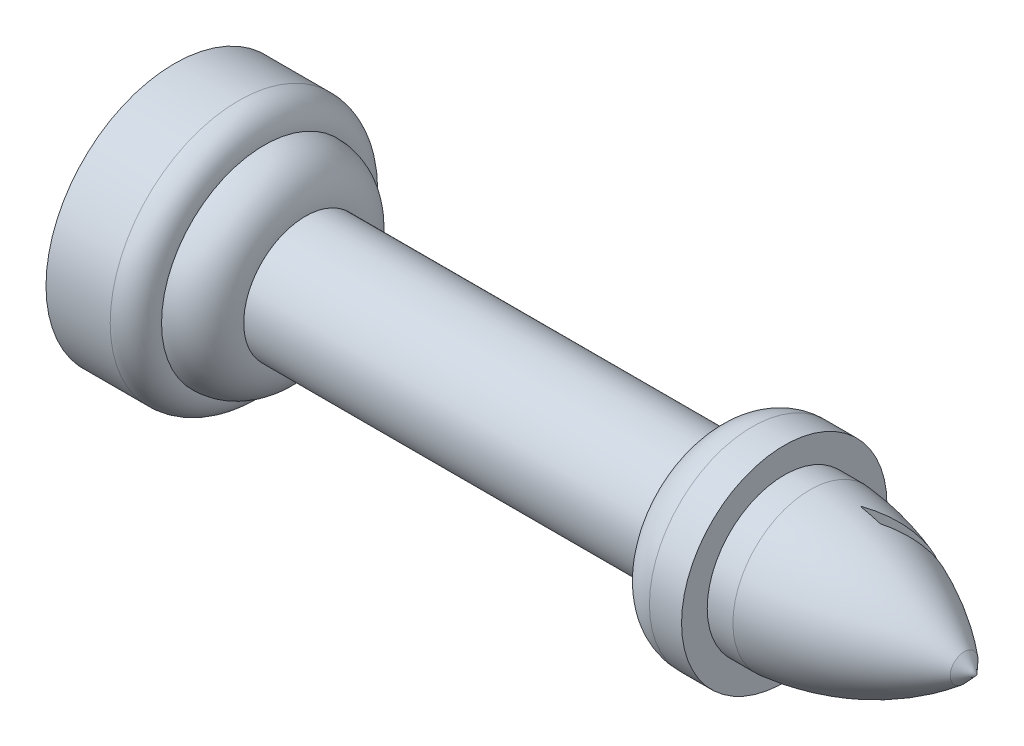
SolidWorks part; units mm, degrees
ref_plane "Спереди" through (0, 0, 0) normal (0, 0, 1) x (1, 0, 0)
ref_plane "Сверху" through (0, 0, 0) normal (0, 1, 0) x (1, 0, 0)
ref_plane "Справа" through (0, 0, 0) normal (1, 0, 0) x (0, 0, -1)
sketch "попа" plane through (0, 0, 0) normal (0, 1, 0) x (1, 0, 0)
  line L0 (0, 0) -> (0, 10)
  line L1 (0, 10) -> (5, 10)
  line L2 (5, 10) -> (5, 0)
  line L3 (-5.61, 0) -> (5.61, 0) construction
  line L5 (7, 0) -> (7, 8)
  line L6 (10.2, 4.8) -> (10.2, 0)
  line L7 (1, 5.25) -> (1, 0)
  line L8 (1, 5.25) -> (3.5, 5.25)
  line L9 (3.5, 5.25) -> (3.5, 0)
  line L10 (0, 0) -> (10.2, 0)
  arc A0 (5, 10) -> (7, 8) centre (5, 8) cw
  arc A1 (7, 8) -> (10.2, 4.8) centre (7, 4.8) cw
  dimension "D3" = 2
  dimension "D5" = 3.2
  dimension "D1" = 10
  dimension "D2" = 5
  dimension "D4" = 2
  dimension "D6" = 4.8
  dimension "D7" = 1
  dimension "D8" = 2.5
  dimension "D9" = 5.25
  dimension "D10" = 5
sketch "верх" plane through (0, 0, 0) normal (0, 1, 0) x (1, 0, 0)
  line L0 (10.2, 4.8) -> (41.8, 4.8)
  line L1 (41.8, 4.8) -> (41.8, 0)
  line L2 (41.8, 0) -> (10.2, 0)
  line L3 (10.2, 0) -> (10.2, 4.8)
  line L4 (45, 0) -> (45, 8)
  line L5 (41.8, 0) -> (45, 0)
  line L6 (45, 8) -> (47.5, 8)
  line L7 (47.5, 8) -> (47.5, 0)
  line L8 (47.5, 0) -> (45, 0)
  arc A0 (41.8, 4.8) -> (45, 8) centre (45, 4.8) cw
  dimension "D2" = 3.2
  dimension "D1" = 31.6
  dimension "D3" = 3.2
  dimension "D4" = 2.5
  dimension "D5" = 8
sketch "верхушка" plane through (0, 0, 0) normal (0, 1, 0) x (1, 0, 0)
  line L0 (47.5, 6) -> (49.5, 6)
  line L1 (47.5, 8) -> (47.5, 0) construction
  line L2 (47.5, 0) -> (47.5, 6)
  line L3 (47.5, 0) -> (62.5, 0)
  line L4 (-55, 0) -> (55, 0) construction
  line L5 (62.5, 0) -> (61.5089, 1.0826)
  arc A0 (49.5, 6) -> (61.5089, 1.0826) centre (47.5386, -15.9124) cw
  point P6 (59.7398, 2.1579)
  point P13 (0, 0)
  point P14 (0, 0)
  point P15 (59.4936, 1.6681)
  point P16 (61.0089, 1.0826)
  dimension "D1" = 22
  dimension "D2" = 2
  dimension "D3" = 6
  dimension "D4" = 15
  dimension "D5" = 1.4677
  dimension "D6" = 1.0826
revolve "Повернуть1" add sketch "верхушка" angle 360 about L3
revolve "Повернуть2" add sketch "верх" angle 360 about L2
revolve "Повернуть3" add sketch "попа" angle 360 about L10
sketch "рот" plane through (0, 0, 0) normal (0, 1, 0) x (1, 0, 0)
  line L0 (52, 1.4) -> (55.2804, 4.6804)
  line L1 (53.6, 1.4) -> (52, 1.4)
  line L2 (53.6, 1.4) -> (56.4167, 4.2167)
  line L3 (49.5, -6) -> (49.5, 6) construction
  line L4 (-11, 0) -> (11, 0) construction
  line L5 (49.5, 1.4) -> (61.0618, 1.4) construction
  arc A2 (61.5089, 1.0826) -> (49.5, 6) centre (47.5386, -15.9124) ccw construction
  arc A3 (55.2804, 4.6804) -> (56.4167, 4.2167) centre (47.5386, -15.9124) cw
  dimension "D6" = 22
  dimension "D1" = 2.5
  dimension "D2" = 1.4
  dimension "D3" = 1.6
  dimension "D4" = 45
  dimension "D5" = 45
extrude "Вырез-Вытянуть3" cut sketch "рот" against normal blind 10
mirror "Зеркальное отражение1" about plane through (47.5386, 0, 15.9124) normal (0, -1, 0) of "Вырез-Вытянуть3"
